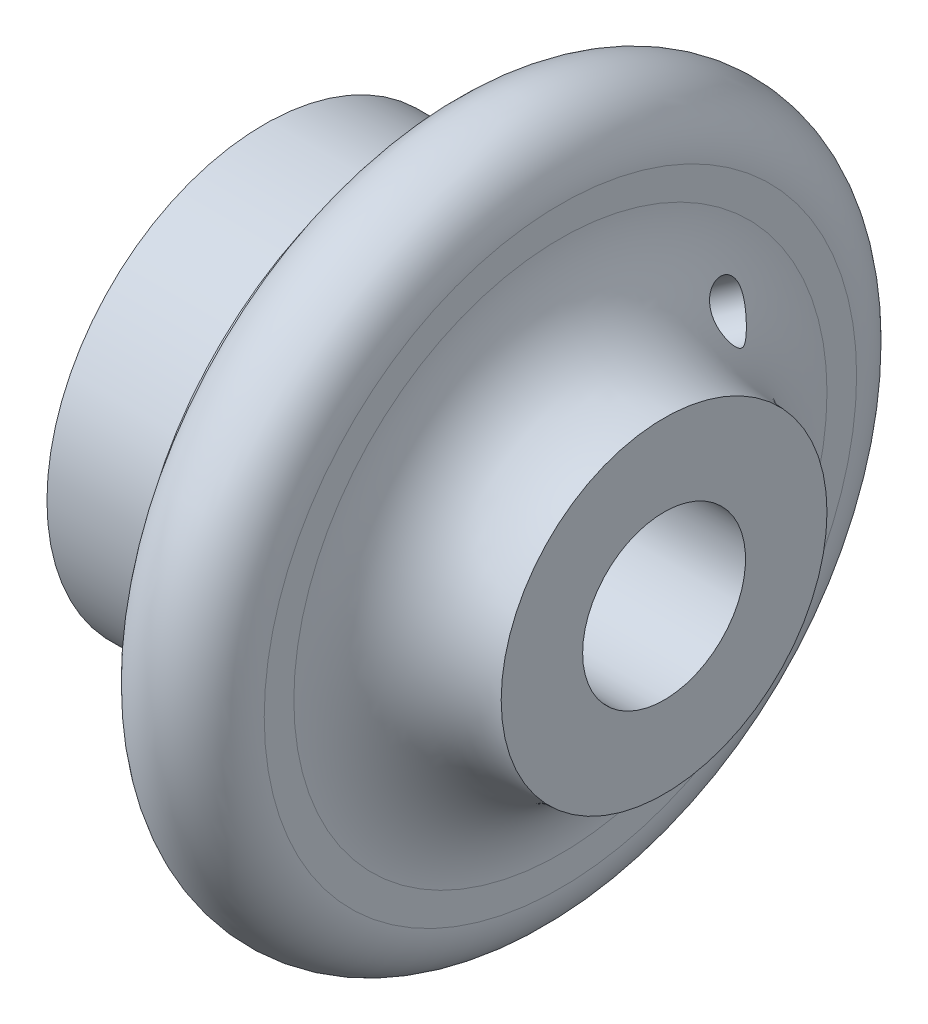
SolidWorks part; units mm, degrees
ref_plane "Front Plane" through (0, 0, 0) normal (0, 0, 1) x (1, 0, 0)
ref_plane "Top Plane" through (0, 0, 0) normal (0, 1, 0) x (1, 0, 0)
ref_plane "Right Plane" through (0, 0, 0) normal (1, 0, 0) x (0, 0, -1)
sketch "Sketch1" plane through (0, 0, 0) normal (0, 0, 1) x (1, 0, 0)
  line L0 (0, 0) -> (41.9403, 0) construction
  line L1 (0, 14.67) -> (0, 5.5)
  line L2 (0, 14.67) -> (8, 14.67)
  line L3 (8, 14.67) -> (8, 13.17)
  line L4 (8, 13.17) -> (11, 13.17)
  line L5 (11, 13.17) -> (11, 20)
  line L6 (11, 20) -> (12, 20)
  line L7 (20, 20) -> (20, 18)
  line L8 (27, 11) -> (27, 5.5)
  line L9 (27, 5.5) -> (0, 5.5)
  arc A0 (12, 20) -> (20, 20) centre (16, 20) cw
  arc A1 (20, 18) -> (27, 11) centre (27, 18) ccw
  point P15 (27.179, 9.3745)
  point P17 (0, 0)
  point P18 (11.858, 24.1358)
  point P19 (14.4461, 24.3088)
  dimension "D7" = 4
  dimension "D9" = 7
  dimension "D1" = 27
  dimension "D2" = 5.5
  dimension "D3" = 14.67
  dimension "D4" = 11
  dimension "D5" = 1.5
  dimension "D6" = 8
  dimension "D8" = 1
  dimension "D10" = 20
revolve "Revolve1" add sketch "Sketch1" angle 360 about L0
cosmetic thread "Cosmetic Thread1" parameters "D1"=8, "D2"=24.2545
hole_wizard "Ø3.6 (3.6) Diameter Hole1" positions "3DSketch1" profile "Sketch2" hole size "Ø3.6" standard "ANSI Metric"
sketch3d "3DSketch1"
  point P0 (21.4726, 9.4495, -9.9263)
sketch "Sketch2" plane through (21.4726, 9.4495, -9.9263) normal (0.0191, 0.707, 0.707) x (-0.6133, 0.5667, -0.5502)
  line L0 (0, 0) -> (0, 13.0815)
  line L1 (0, 13.0815) -> (1.8, 12)
  line L2 (1.8, 12) -> (1.8, 0)
  line L5 (1.8, 0) -> (0, 0)
  line L10 (0, 13.0815) -> (-1.8, 12) construction
  line L11 (0, -6.35) -> (0, 107.95) construction
  dimension "Hole Dia." = 3.6
  dimension "Hole Depth" = 12
  dimension "Drill Angle" = 118
